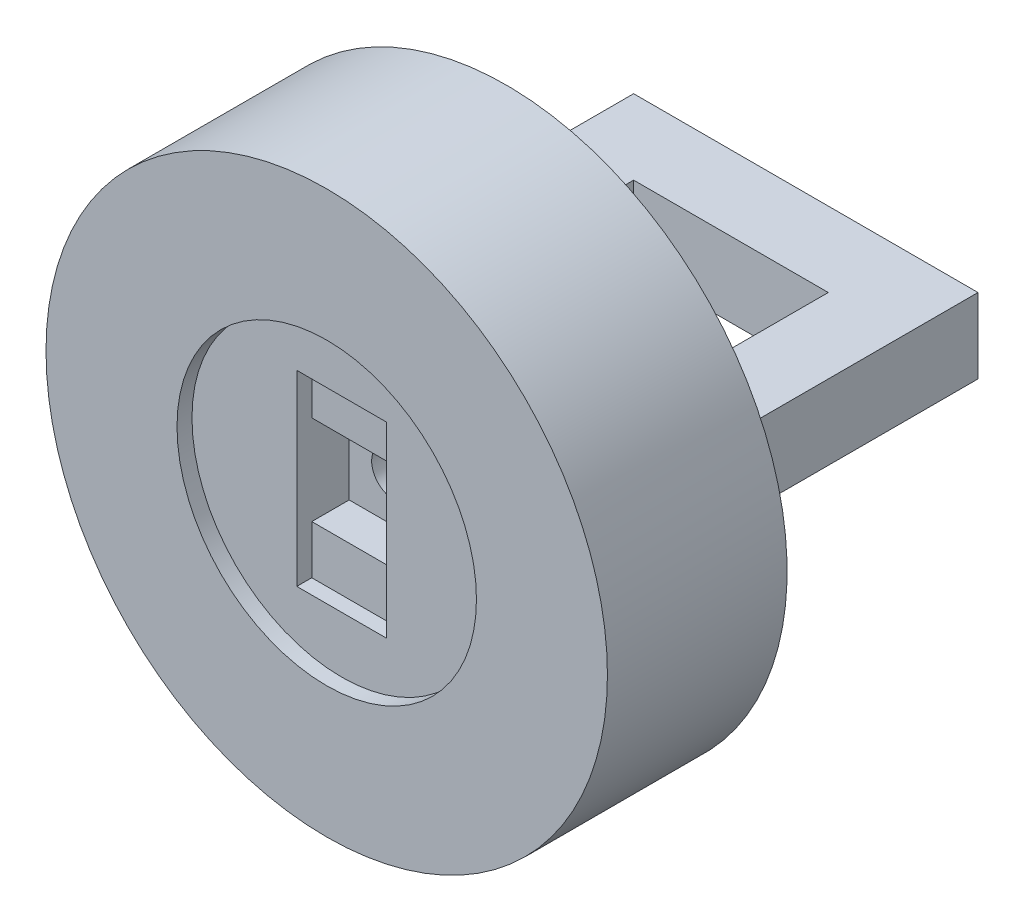
SolidWorks part; units mm, degrees
ref_plane "Спереди" through (0, 0, 0) normal (0, 0, 1) x (1, 0, 0)
ref_plane "Сверху" through (0, 0, 0) normal (0, 1, 0) x (1, 0, 0)
ref_plane "Справа" through (0, 0, 0) normal (1, 0, 0) x (0, 0, -1)
sketch "Эскиз1" plane through (0, 0, 0) normal (0, 0, 1) x (1, 0, 0)
  circle A0 centre (0, 0) radius 37.5
  circle A1 centre (0, 0) radius 3
  dimension "D1" = 75
extrude "Бобышка-Вытянуть1" add sketch "Эскиз1" along normal blind 5
sketch "Эскиз2" plane through (0, 0, 0) normal (0, 0, -1) x (-1, 0, 0)
  circle A0 centre (0, 0) radius 37.5
  dimension "D1" = 75
extrude "Бобышка-Вытянуть2" add sketch "Эскиз2" along normal blind 10
sketch "Эскиз4" plane through (0, 0, 5) normal (0, 0, 1) x (1, 0, 0)
  line L1 (-6, -6) -> (6, -6)
  line L2 (-6, -6) -> (-6, 6)
  line L3 (-6, 6) -> (6, 6)
  line L4 (6, -6) -> (6, 6)
  line L5 (0, 6) -> (0, -6) construction
  line L6 (-6, 0) -> (6, 0) construction
  circle A0 centre (0, 0) radius 37.5
  point P6 (0, 6)
  point P7 (0, 0)
  dimension "D3" = 75
  dimension "D1" = 12
  dimension "D2" = 12
extrude "Бобышка-Вытянуть3" add sketch "Эскиз4" along normal blind 5
sketch "Эскиз6" plane through (0, 0, 10) normal (0, 0, 1) x (1, 0, 0)
  line L1 (-6, -12.5) -> (6, -12.5)
  line L2 (-6, -12.5) -> (-6, 12.5)
  line L3 (-6, 12.5) -> (6, 12.5)
  line L4 (6, -12.5) -> (6, 12.5)
  line L5 (0, 12.5) -> (0, -12.5) construction
  line L6 (-6, 0) -> (6, 0) construction
  circle A0 centre (0, 0) radius 37.5
  dimension "D1" = 75
  dimension "D2" = 25
extrude "Бобышка-Вытянуть4" add sketch "Эскиз6" along normal blind 2
sketch "Эскиз11" plane through (0, 0, 12) normal (0, 0, 1) x (1, 0, 0)
  circle A0 centre (0, 0) radius 20
  circle A1 centre (0, 0) radius 37.5
extrude "Бобышка-Вытянуть6" add sketch "Эскиз11" along normal blind 2
sketch "Эскиз13" plane through (0, 0, -10) normal (0, 0, -1) x (-1, 0, 0)
  line L1 (-13, -5) -> (-23, -5)
  line L2 (-13, -5) -> (-13, 5)
  line L3 (-13, 5) -> (-23, 5)
  line L4 (-23, -5) -> (-23, 5)
  line L5 (-18, 5) -> (-18, -5) construction
  line L6 (-13, 0) -> (-23, 0) construction
  line L11 (23, -5) -> (13, -5)
  line L12 (23, -5) -> (23, 5)
  line L13 (23, 5) -> (13, 5)
  line L14 (13, -5) -> (13, 5)
  line L15 (18, 5) -> (18, -5) construction
  line L16 (23, 0) -> (13, 0) construction
  point P0 (-18, 0)
  point P4 (0, 0)
  point P5 (18, 0)
  dimension "D1" = 10
  dimension "D2" = 10
  dimension "D3" = 10
  dimension "D4" = 10
extrude "Бобышка-Вытянуть7" add sketch "Эскиз13" along normal blind 30
sketch "Эскиз14" plane through (0, 0, -40) normal (0, 0, -1) x (-1, 0, 0)
  line L1 (-23, -5) -> (23, -5)
  line L2 (-23, -5) -> (-23, 5)
  line L3 (-23, 5) -> (23, 5)
  line L4 (23, -5) -> (23, 5)
extrude "Бобышка-Вытянуть8" add sketch "Эскиз14" along normal blind 10
